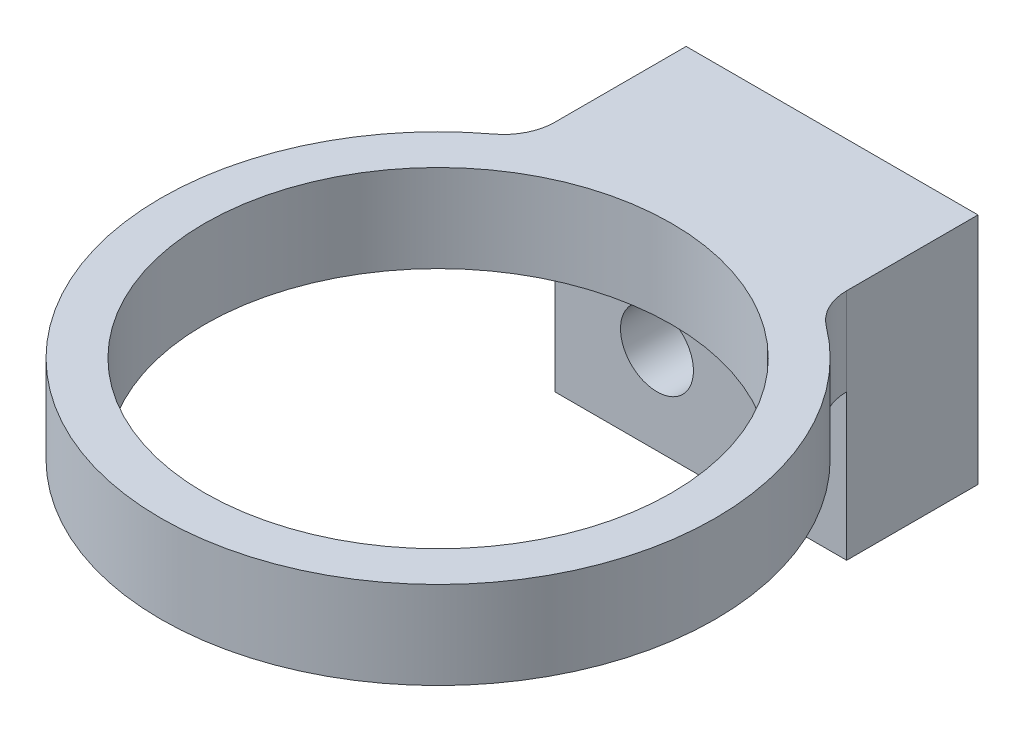
SolidWorks part; units mm, degrees
material "6061 Alloy"
ref_plane "Front Plane" through (0, 0, 0) normal (0, 0, 1) x (1, 0, 0)
ref_plane "Top Plane" through (0, 0, 0) normal (0, 1, 0) x (1, 0, 0)
ref_plane "Right Plane" through (0, 0, 0) normal (1, 0, 0) x (0, 0, -1)
ref_plane "Plane1" through (0, 0, 0) normal (0, -1, 0) x (1, 0, 0)
sketch "Sketch1" plane through (0, 0, 0) normal (0, -1, 0) x (1, 0, 0)
  line L0 (-5, 5.4223) -> (-5, 0)
  line L1 (-5, 0) -> (5, 0)
  line L2 (5, 0) -> (5, 5.4223)
  arc A0 (5, 5.4223) -> (-5, 5.4223) centre (0, 13.5) ccw
extrude "Boss-Extrude1" add sketch "Sketch1" against normal blind 3
sketch "Sketch2" plane through (0, 0, 0) normal (0, -1, 0) x (1, 0, 0)
  line L0 (-5, 0) -> (-5, 4.5)
  line L1 (-5, 4.5) -> (5, 4.5)
  line L2 (5, 4.5) -> (5, 0)
  line L3 (5, 0) -> (-5, 0)
extrude "Boss-Extrude2" add sketch "Sketch2" along normal blind 5
hole_wizard "M2x0.4 Tapped Hole1" positions "Sketch4" profile "Sketch3" tap size "M2x0.4" standard "ANSI Metric"
sketch "Sketch4" plane through (0, 0, 0) normal (0, 0, -1) x (-1, 0, 0)
  point P0 (-3, 1)
sketch "Sketch3" plane through (3, 1, 0) normal (1, 0, 0) x (0, 1, 0)
  line L0 (0, 0) -> (0, 5.6807)
  line L1 (0, 5.6807) -> (0.8, 5.2)
  line L2 (0.8, 5.2) -> (0.8, 0)
  line L5 (0.8, 0) -> (0, 0)
  line L10 (0, 5.6807) -> (-0.8, 5.2) construction
  line L11 (0, -6.35) -> (0, 107.95) construction
  dimension "Tap Drill Dia." = 1.6
  dimension "Tap Drill Depth" = 5.2
  dimension "Drill Angle" = 118
hole_wizard "M3x0.5 Tapped Hole1" positions "Sketch6" profile "Sketch5" tap size "M3x0.5" standard "ANSI Metric" end condition through all
sketch "Sketch6" plane through (0, 0, 4.5) normal (0, 0, 1) x (1, 0, 0)
  point P0 (-1.5, -2)
sketch "Sketch5" plane through (-1.5, -2, 4.5) normal (1, 0, 0) x (0, -1, 0)
  line L0 (0, 0) -> (0, 4.5)
  line L1 (0, 4.5) -> (1.25, 4.5)
  line L2 (1.25, 4.5) -> (1.25, 0)
  line L5 (1.25, 0) -> (0, 0)
  line L11 (0, -6.35) -> (0, 107.95) construction
  dimension "Thread Major Dia." = 2.5
  dimension "Thru Tap Drill Depth" = 4.5
hole_wizard "M14 Clearance Hole1" positions "Sketch8" profile "Sketch7" hole size "M14" standard "ANSI Metric" end condition through all
sketch "Sketch8" plane through (0, 0, 0) normal (0, -1, 0) x (-1, 0, 0)
  point P0 (0, -13.5)
sketch "Sketch7" plane through (0, 0, 13.5) normal (1, 0, 0) x (0, 0, -1)
  line L0 (0, 0) -> (0, 3)
  line L1 (0, 3) -> (8, 3)
  line L2 (8, 3) -> (8, 0)
  line L5 (8, 0) -> (0, 0)
  line L11 (0, -6.35) -> (0, 107.95) construction
  dimension "Thru Hole Dia." = 16
  dimension "Thru Hole Depth" = 3
fillet "Fillet1" radius 1.75 2 edges at (-5, 1.5, 5.4223) (5, 1.5, 5.4223)
